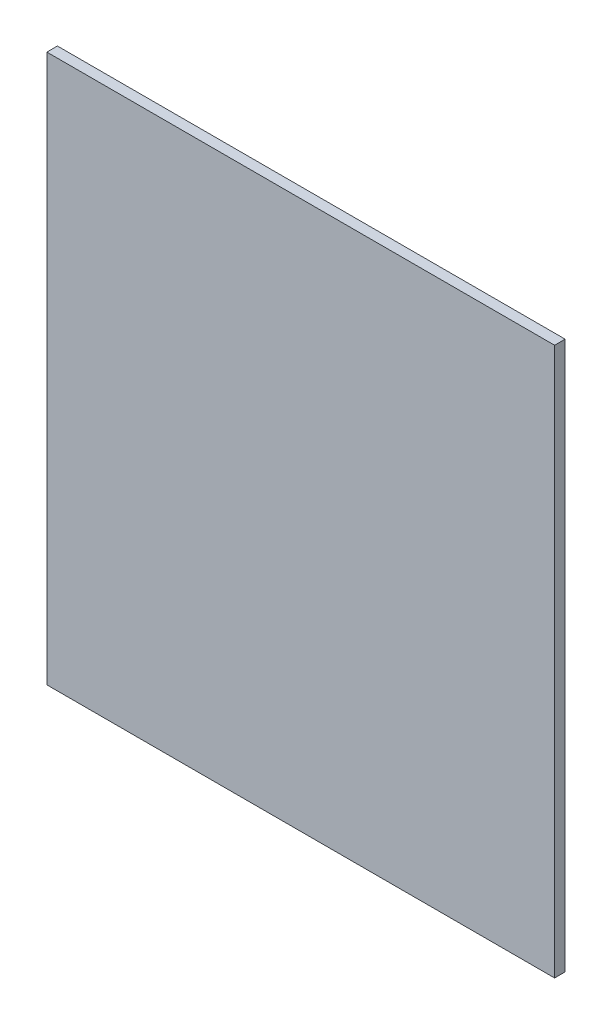
SolidWorks part; units mm, degrees
ref_plane "Front Plane" through (0, 0, 0) normal (0, 0, 1) x (1, 0, 0)
ref_plane "Top Plane" through (0, 0, 0) normal (0, 1, 0) x (1, 0, 0)
ref_plane "Right Plane" through (0, 0, 0) normal (1, 0, 0) x (0, 0, -1)
sketch "Sketch1" plane through (0, 0, 0) normal (0, 0, 1) x (1, 0, 0)
  line L1 (-24.09, -26) -> (24.09, -26)
  line L2 (-24.09, -26) -> (-24.09, 26)
  line L3 (-24.09, 26) -> (24.09, 26)
  line L4 (24.09, -26) -> (24.09, 26)
  line L5 (-24.09, -26) -> (24.09, 26) construction
  line L6 (-24.09, 26) -> (24.09, -26) construction
  point P0 (0, 0)
  dimension "D1" = 48.18
  dimension "D2" = 52
extrude "Boss-Extrude1" add sketch "Sketch1" along normal blind 1
